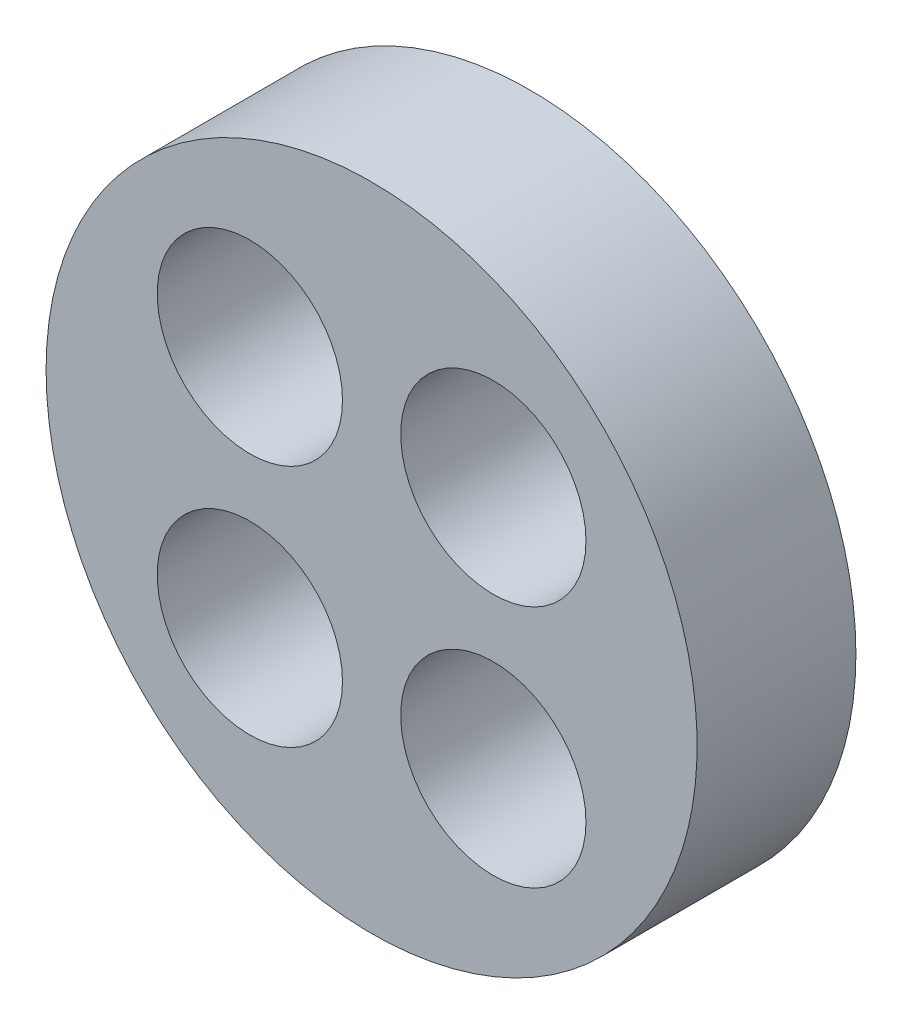
SolidWorks part; units mm, degrees
ref_plane "Front Plane" through (0, 0, 0) normal (0, 0, 1) x (1, 0, 0)
ref_plane "Top Plane" through (0, 0, 0) normal (0, 1, 0) x (1, 0, 0)
ref_plane "Right Plane" through (0, 0, 0) normal (1, 0, 0) x (0, 0, -1)
sketch "Sketch1" plane through (0, 0, 0) normal (1, 0, 0) x (0, 0, -1)
  line L0 (-0.1016, 0) -> (-1.6891, 0) construction
  line L1 (12.5984, 1.5875) -> (-0.1016, 1.5875)
  line L2 (12.5984, 1.5875) -> (12.5984, 0)
  line L3 (12.5984, 0) -> (-0.1016, 0)
  line L4 (-0.1016, 1.5875) -> (-0.1016, 0)
  dimension "D1" = 0.1016
  dimension "D2" = 3.175
  dimension "D3" = 12.7
revolve "Revolve1" add sketch "Sketch1" angle 360 about L0
sketch "Sketch2" plane through (0, 0, 0) normal (1, 0, 0) x (0, 0, -1)
  line L0 (0, 0) -> (0, 1.5621)
  line L1 (0, 1.5621) -> (4.4415, 1.5621)
  line L2 (4.4415, 1.5621) -> (5.3148, 2.4354)
  line L3 (5.3148, 2.4354) -> (-1.4322, 2.4354)
  line L4 (-1.4322, 2.4354) -> (-1.4322, 0)
  line L5 (-1.4322, 0) -> (0, 0)
  line L6 (-1.4322, 0) -> (-2.9449, 0) construction
  dimension "D1" = 45
  dimension "D2" = 3.1242
revolve "Cut-Revolve1" cut sketch "Sketch2" angle 360 about L6
hole_wizard "#65 (0.035) Diameter Hole1" positions "Sketch4" profile "Sketch3" hole size "#65" standard "ANSI Inch"
sketch "Sketch4" plane through (0, 0, 0) normal (0, 0, 1) x (1, 0, 0)
  point P0 (0.5842, 0.5842)
  point P2 (-0.5842, 0.5842)
  point P4 (-0.5842, -0.5842)
  point P6 (0.5842, -0.5842)
  dimension "D1" = 0.5842
  dimension "D2" = 0.5842
  dimension "D3" = 0.5842
  dimension "D4" = 0.5842
sketch "Sketch3" plane through (0.5842, 0.5842, 0) normal (1, 0, 0) x (0, -1, 0)
  line L0 (0, 0) -> (0, 9.7921)
  line L1 (0, 9.7921) -> (0.4445, 9.525)
  line L2 (0.4445, 9.525) -> (0.4445, 0)
  line L5 (0.4445, 0) -> (0, 0)
  line L10 (0, 9.7921) -> (-0.4445, 9.525) construction
  line L11 (0, -6.35) -> (0, 107.95) construction
  dimension "Hole Dia." = 0.889
  dimension "Hole Depth" = 9.525
  dimension "Drill Angle" = 118
sketch "Sketch5" plane through (0, 0, 0) normal (1, 0, 0) x (0, 0, -1)
  line L1 (0.762, 7.62) -> (16.002, 7.62)
  line L2 (0.762, 7.62) -> (0.762, -7.62)
  line L3 (0.762, -7.62) -> (16.002, -7.62)
  line L4 (16.002, 7.62) -> (16.002, -7.62)
  point P4 (0.762, 0)
  dimension "D1" = 0.762
  dimension "D2" = 15.24
extrude "Cut-Extrude1" cut sketch "Sketch5" against normal mid plane 7.62
chamfer "Chamfer1" [suppressed] distance 0.1016 angle 45
